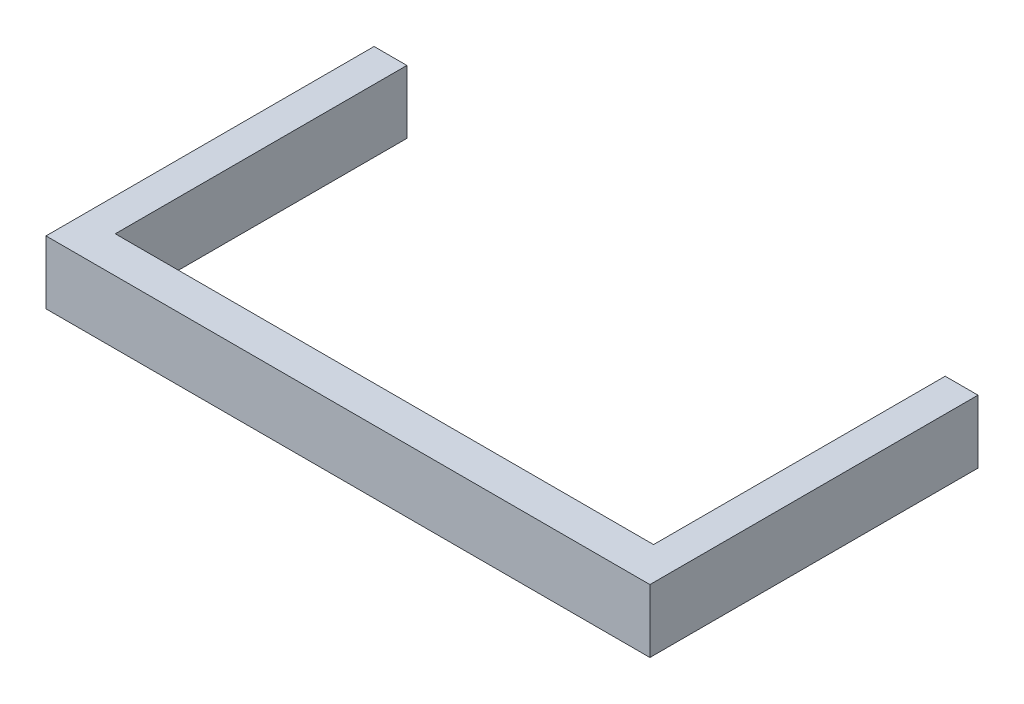
SolidWorks part; units mm, degrees
ref_plane "Front Plane" through (0, 0, 0) normal (0, 0, 1) x (1, 0, 0)
ref_plane "Top Plane" through (0, 0, 0) normal (0, 1, 0) x (1, 0, 0)
ref_plane "Right Plane" through (0, 0, 0) normal (1, 0, 0) x (0, 0, -1)
sketch "Sketch1" plane through (0, 0, 0) normal (0, 0, 1) x (1, 0, 0)
  line L1 (0, 0) -> (2.7, 0)
  line L2 (0, 0) -> (0, 5.2)
  line L3 (0, 5.2) -> (2.7, 5.2)
  line L4 (2.7, 0) -> (2.7, 5.2)
  dimension "D1" = 5.2
  dimension "D2" = 2.7
extrude "Boss-Extrude1" add sketch "Sketch1" along normal blind 27
sketch "Sketch2" plane through (0, 0, 0) normal (-1, 0, 0) x (0, 0, 1)
  line L5 (27, 5.2) -> (24, 5.2)
  line L6 (27, 5.2) -> (27, 0) construction
  line L7 (24, 5.2) -> (24, 0)
  line L8 (24, 0) -> (27, 0)
  line L9 (27, 0) -> (27, 5.2)
  line L10 (27, 5.2) -> (0, 5.2) construction
  line L11 (27, 0) -> (0, 0) construction
  dimension "D1" = 3
  dimension "D2" = 0
  dimension "D3" = 0
extrude "Boss-Extrude2" add sketch "Sketch2" along normal blind 47
sketch "Sketch3" plane through (0, 0, 24) normal (0, 0, -1) x (-1, 0, 0)
  line L0 (47, 0) -> (0, 0) construction
  line L1 (47, 5.2) -> (44.3, 5.2)
  line L2 (47, 5.2) -> (47, 0)
  line L3 (47, 0) -> (44.3, 0)
  line L4 (44.3, 5.2) -> (44.3, 0)
  dimension "D1" = 2.7
extrude "Boss-Extrude3" add sketch "Sketch3" along normal blind 24
